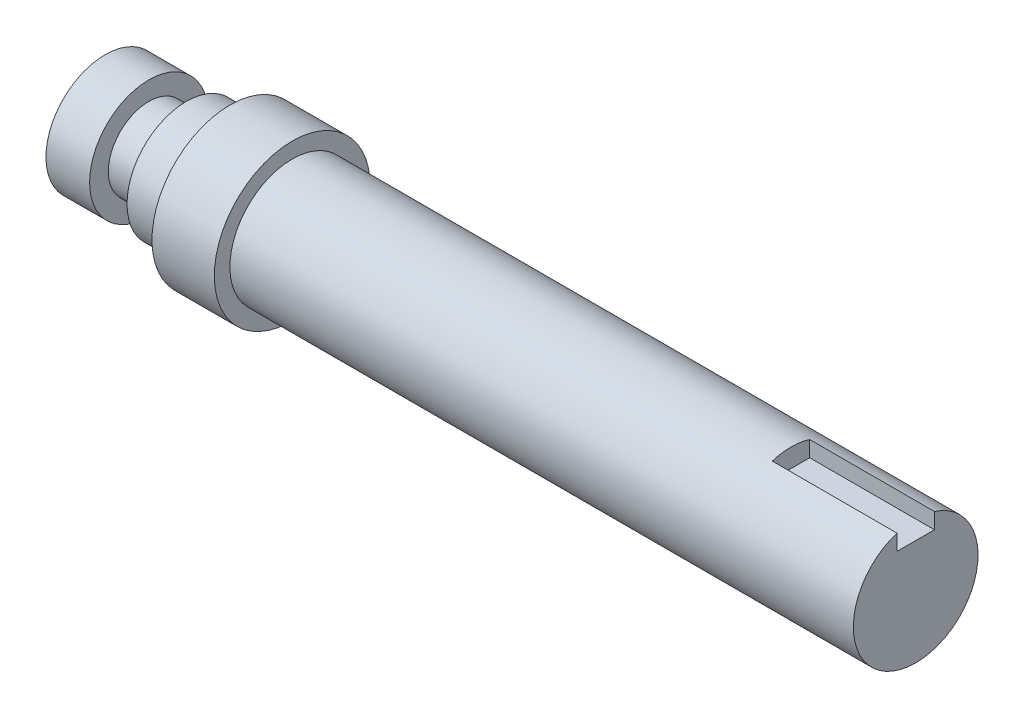
SolidWorks part; units mm, degrees
ref_plane "Front Plane" through (0, 0, 0) normal (0, 0, 1) x (1, 0, 0)
ref_plane "Top Plane" through (0, 0, 0) normal (0, 1, 0) x (1, 0, 0)
ref_plane "Right Plane" through (0, 0, 0) normal (1, 0, 0) x (0, 0, -1)
sketch "Sketch1" plane through (0, 0, 0) normal (0, 0, 1) x (1, 0, 0)
  line L0 (0, 0) -> (-130, 0)
  line L1 (-130, 0) -> (-130, 9.5)
  line L2 (-130, 9.5) -> (-110, 9.5)
  line L3 (-110, 9.5) -> (-110, 12.5)
  line L4 (-110, 12.5) -> (-100, 12.5)
  line L5 (-100, 12.5) -> (-100, 10)
  line L6 (-100, 10) -> (0, 10)
  line L7 (0, 10) -> (0, 0)
  dimension "D1" = 100
  dimension "D2" = 20
  dimension "D3" = 10
  dimension "D4" = 10
  dimension "D5" = 9.5
  dimension "D6" = 12.5
revolve "Revolve1" add sketch "Sketch1" angle 360 about L0
sketch "Sketch2" plane through (0, 0, 0) normal (0, 0, 1) x (1, 0, 0)
  line L0 (-110, 9.5) -> (-130, 9.5) construction
  line L1 (-117, 9.5) -> (-123, 9.5)
  line L2 (-117, 9.5) -> (-117, 6.5)
  line L3 (-117, 6.5) -> (-123, 6.5)
  line L4 (-123, 9.5) -> (-123, 6.5)
  line L5 (-130, 9.5) -> (-130, -9.5) construction
  line L6 (-130, 0) -> (-103.3551, 0) construction
  dimension "D1" = 6
  dimension "D2" = 3
  dimension "D3" = 7
revolve "Cut-Revolve1" cut sketch "Sketch2" angle 360 about L6
sketch "Sketch3" plane through (0, 0, 0) normal (0, 0, 1) x (1, 0, 0)
  line L0 (0, 10) -> (-100, 10) construction
  line L1 (0, 12) -> (-20, 12)
  line L2 (0, 12) -> (0, 7)
  line L3 (0, 7) -> (-20, 7)
  line L4 (-20, 12) -> (-20, 7)
  line L5 (0, -10) -> (0, 10) construction
  dimension "D1" = 3
  dimension "D2" = 20
  dimension "D3" = 20
  dimension "D4" = 5
extrude "Cut-Extrude1" cut sketch "Sketch3" against normal mid plane 6
